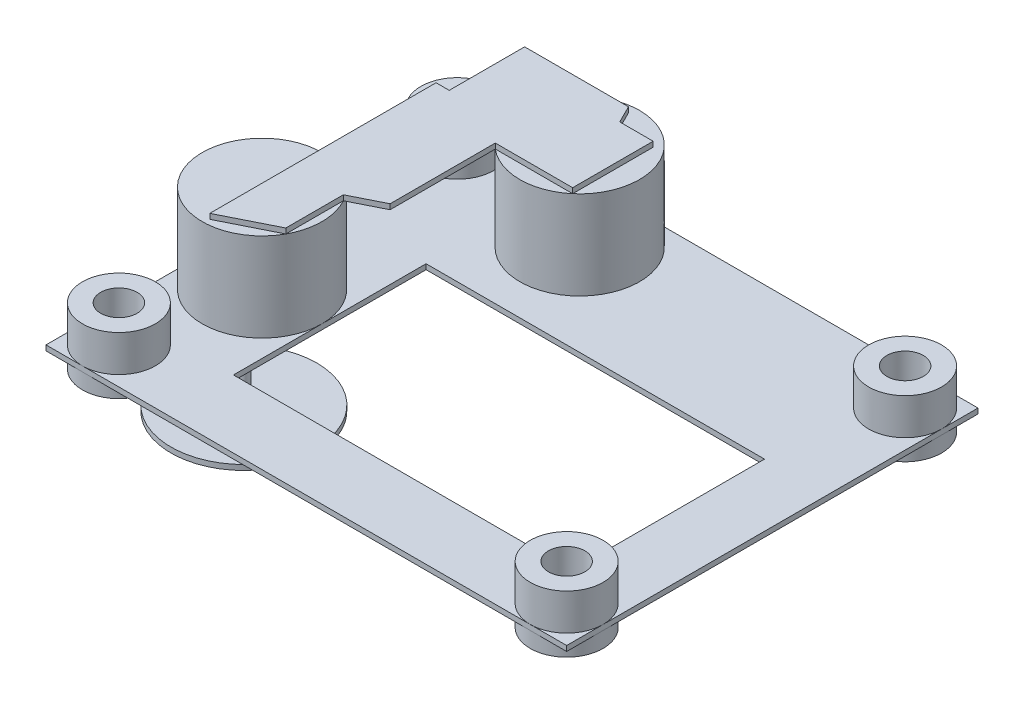
SolidWorks part; units mm, degrees
ref_plane "Plan de face" through (0, 0, 0) normal (0, 0, 1) x (1, 0, 0)
ref_plane "Plan de dessus" through (0, 0, 0) normal (0, 1, 0) x (1, 0, 0)
ref_plane "Plan de droite" through (0, 0, 0) normal (1, 0, 0) x (0, 0, -1)
sketch "Esquisse4" plane through (0, 0, 0) normal (0, 1, 0) x (1, 0, 0)
  line L1 (-50, -39.5) -> (50, -39.5)
  line L2 (-50, -39.5) -> (-50, 39.5)
  line L3 (-50, 39.5) -> (50, 39.5)
  line L4 (50, -39.5) -> (50, 39.5)
  line L5 (-50, -39.5) -> (50, 39.5) construction
  line L6 (-50, 39.5) -> (50, -39.5) construction
  point P0 (0, 0)
  dimension "D1" = 100
  dimension "D2" = 79
extrude "Boss.-Extru.3" add sketch "Esquisse4" against normal blind 1
sketch "Esquisse1" plane through (0, 0, 0) normal (0, 1, 0) x (1, 0, 0)
  line L0 (36, 39.5) -> (36, 25.5) construction
  line L1 (-50, -39.5) -> (50, -39.5)
  line L2 (-50, -39.5) -> (-50, 39.5)
  line L3 (-50, 39.5) -> (50, 39.5)
  line L4 (50, -39.5) -> (50, 39.5)
  line L5 (-50, -39.5) -> (50, 39.5) construction
  line L6 (-50, 39.5) -> (50, -39.5) construction
  line L7 (36, 25.5) -> (50, 25.5) construction
  line L8 (36, 25.5) -> (50, 39.5) construction
  line L9 (-36, 39.5) -> (-36, 25.5) construction
  line L10 (-36, 25.5) -> (-50, 25.5) construction
  line L11 (-36, 25.5) -> (-50, 39.5) construction
  line L12 (-50, -25.5) -> (-36, -25.5) construction
  line L13 (-36, -25.5) -> (-36, -39.5) construction
  line L14 (-36, -25.5) -> (-50, -39.5) construction
  line L15 (50, -25.5) -> (36, -25.5) construction
  line L16 (36, -25.5) -> (36, -39.5) construction
  line L17 (36, -25.5) -> (50, -39.5) construction
  circle A0 centre (43, 32.5) radius 7
  circle A1 centre (-43, 32.5) radius 7
  circle A2 centre (-43, -32.5) radius 7
  circle A3 centre (43, -32.5) radius 7
  circle A4 centre (-43, 32.5) radius 3.5
  circle A5 centre (43, 32.5) radius 3.5
  circle A6 centre (43, -32.5) radius 3.5
  circle A7 centre (-43, -32.5) radius 3.5
  point P0 (0, 0)
  dimension "D4" = 14
  dimension "D5" = 14
  dimension "D12" = 7
  dimension "D13" = 7
  dimension "D14" = 7
  dimension "D15" = 7
  dimension "D1" = 100
  dimension "D2" = 79
  dimension "D3" = 14
  dimension "D6" = 14
  dimension "D7" = 14
  dimension "D8" = 14
  dimension "D9" = 14
  dimension "D10" = 14
  dimension "D11" = 14
extrude "Boss.-Extru.4" add sketch "Esquisse1" against normal blind 4 and the other way blind 7 contours A0 | A1 | A2 | A3
sketch "Esquisse6" plane through (0, 0, 0) normal (0, 1, 0) x (1, 0, 0)
  line L0 (-38.5, -9.5) -> (-50, -9.5) construction
  line L1 (-50, 32.5) -> (-50, -32.5) construction
  line L2 (-38.5, -9.5) -> (-38.5, -39.5) construction
  line L3 (-43, -39.5) -> (43, -39.5) construction
  line L4 (-15, 28) -> (-15, 39.5) construction
  line L5 (43, 39.5) -> (-43, 39.5) construction
  line L6 (-15, 28) -> (-50, 28) construction
  circle A0 centre (-38.5, -9.5) radius 11.5
  circle A1 centre (-15, 28) radius 11.5
  dimension "D1" = 23
  dimension "D2" = 23
  dimension "D3" = 11.5
  dimension "D4" = 30
  dimension "D5" = 11.5
  dimension "D6" = 35
extrude "Boss.-Extru.5" add sketch "Esquisse6" along normal blind 17
sketch "Esquisse7" plane through (0, 17, 0) normal (0, 1, 0) x (1, 0, 0)
  line L0 (-38.1438, -19.8875) -> (-28.4142, -15.0251)
  line L1 (-28.4142, -15.0251) -> (-28.4142, -3.9749)
  line L2 (-28.4142, -3.9749) -> (-22.4283, -0.9834)
  line L3 (-22.4283, -0.9834) -> (-22.4283, 19.221)
  line L4 (-22.4283, 19.221) -> (-7.5717, 19.221)
  line L5 (-7.5717, 19.221) -> (-7.5717, 34.6801)
  line L6 (-7.5717, 34.6801) -> (-13.9887, 34.6801)
  line L7 (-13.9887, 34.6801) -> (-15.6674, 38.0391)
  line L8 (-15.6674, 38.0391) -> (-35.6132, 38.0391)
  line L9 (-35.6132, 38.0391) -> (-35.6132, 23.5595)
  line L12 (-38.1438, 23.5595) -> (-38.1438, 0)
  line L13 (-38.1438, 0) -> (-38.1438, -19.8875)
  line L14 (-38.1438, 23.5595) -> (-35.6132, 23.5595)
  circle A0 centre (-38.5, -9.5) radius 11.5 construction
  circle A1 centre (-38.5, -9.5) radius 11.5 construction
  circle A2 centre (-15, 28) radius 11.5 construction
  circle A3 centre (-15, 28) radius 11.5 construction
  point P4 (-38.1438, 23.5595)
extrude "Boss.-Extru.6" add sketch "Esquisse7" along normal blind 1
sketch "Esquisse8" plane through (0, 0, 0) normal (0, 1, 0) x (1, 0, 0)
  line L0 (-43, -39.5) -> (43, -39.5) construction
  line L1 (-27, -26.5) -> (38, -26.5)
  line L2 (-27, -26.5) -> (-27, 10.5)
  line L3 (-27, 10.5) -> (38, 10.5)
  line L4 (38, -26.5) -> (38, 10.5)
  line L5 (50, -32.5) -> (50, 32.5) construction
  dimension "D1" = 13
  dimension "D2" = 37
  dimension "D3" = 65
  dimension "D4" = 12
extrude "Enlèv. mat.-Extru.1" cut sketch "Esquisse8" against normal blind 1
sketch "Esquisse9" plane through (0, -1, 0) normal (0, -1, 0) x (1, 0, 0)
  line L0 (-50, 39.5) -> (-43, 39.5) construction
  line L1 (-50, -32.5) -> (-50, 32.5) construction
  circle A0 centre (-40, 11.5) radius 1
  dimension "D1" = 2
  dimension "D2" = 28
  dimension "D3" = 10
extrude "Boss.-Extru.7" add sketch "Esquisse9" along normal blind 18
sketch "Esquisse10" plane through (0, -19, 0) normal (0, -1, 0) x (1, 0, 0)
  circle A0 centre (-40, 11.5) radius 14
  dimension "D1" = 28
extrude "Boss.-Extru.8" add sketch "Esquisse10" along normal blind 1
sketch "Esquisse11" plane through (0, -20, 0) normal (0, -1, 0) x (-1, 0, 0)
  line L0 (26, -11.5) -> (54, -11.5) construction
  circle A0 centre (40, -11.5) radius 14 construction
  circle A1 centre (40, -11.5) radius 7
  dimension "D1" = 14
extrude "Boss.-Extru.9" add sketch "Esquisse11" along normal blind 2
